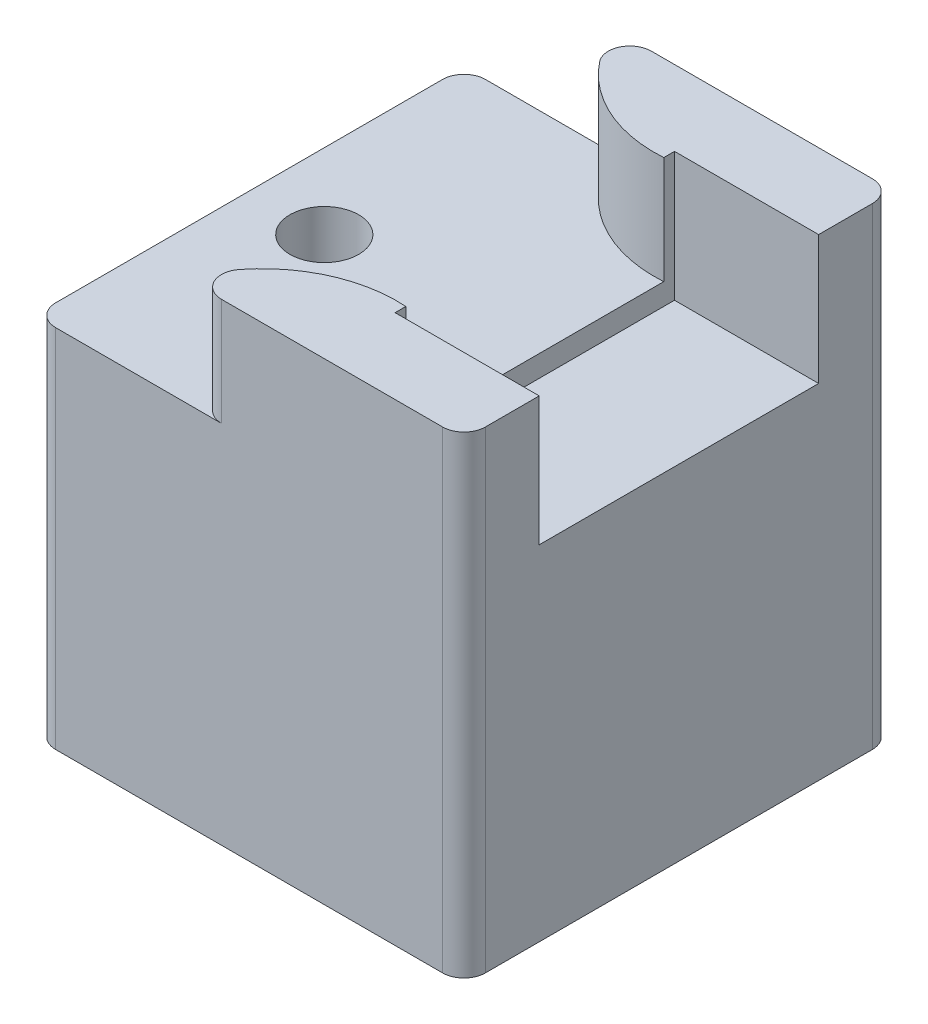
SolidWorks part; units mm, degrees
ref_plane "Alzado" through (0, 0, 0) normal (0, 0, 1) x (1, 0, 0)
ref_plane "Planta" through (0, 0, 0) normal (0, 1, 0) x (1, 0, 0)
ref_plane "Vista lateral" through (0, 0, 0) normal (1, 0, 0) x (0, 0, -1)
sketch "Croquis2" plane through (0, 0, 0) normal (0, 1, 0) x (1, 0, 0)
  line L1 (-10.8434, 8.4739) -> (9.1566, 8.4739)
  line L2 (-10.8434, 8.4739) -> (-10.8434, -11.5261)
  line L3 (-10.8434, -11.5261) -> (9.1566, -11.5261)
  line L4 (9.1566, 8.4739) -> (9.1566, -11.5261)
  dimension "D1" = 20
  dimension "D2" = 20
extrude "Saliente-Extruir1" add sketch "Croquis2" along normal blind 8
sketch "Croquis3" plane through (0, 8, 0) normal (0, 1, 0) x (1, 0, 0)
  line L0 (9.1566, 4.9739) -> (1.1799, 4.9739) construction
  line L1 (9.1566, -11.5261) -> (9.1566, 8.4739) construction
  line L2 (9.1566, -8.0261) -> (5.7192, -8.0261) construction
  line L3 (-10.8434, -11.5261) -> (9.1566, -11.5261) construction
  line L4 (9.1566, 8.4739) -> (-10.8434, 8.4739) construction
  line L6 (9.1566, 4.9739) -> (2.4509, 4.9739)
  line L7 (9.1566, 4.9739) -> (9.1566, -8.0261)
  line L8 (9.1566, -8.0261) -> (2.4509, -8.0261)
  line L9 (2.4509, 4.9739) -> (2.4509, -8.0261)
  dimension "D1" = 3.5
  dimension "D2" = 3.5
extrude "Cortar-Extruir1" cut sketch "Croquis3" against normal blind 6
sketch "Croquis5" plane through (0, 8, 0) normal (0, 1, 0) x (1, 0, 0)
  line L0 (2.4509, 4.9739) -> (-1.2584, 4.9739) construction
  line L1 (2.4509, -8.0261) -> (0, -8.0261) construction
  line L2 (2.4509, 4.9739) -> (2.4509, -8.0261) construction
  line L3 (2.4509, 4.4739) -> (1.59, 4.4739)
  line L4 (2.4509, 4.4739) -> (2.4509, -7.5261)
  line L5 (2.4509, -7.5261) -> (1.59, -7.5261)
  line L7 (-10.8434, 8.4739) -> (9.1566, -11.5261) construction
  line L8 (-0.8434, -1.5261) -> (2.4509, -1.5261) construction
  line L9 (9.1566, 8.4739) -> (-10.8434, 8.4739) construction
  arc A0 (2.4509, 4.4739) -> (-3.8325, 8.4739) centre (2.0204, 10.7329) cw
  arc A1 (2.4509, -7.5261) -> (-3.8325, -11.5261) centre (2.0204, -13.7851) ccw
  line M7 (2.4509, -8.0261) -> (2.4509, 4.9739)
  line M10 (9.1566, 8.4739) -> (-10.8434, 8.4739)
  line M11 (-10.8434, 8.4739) -> (-10.8434, -11.5261)
  line M12 (-10.8434, -11.5261) -> (9.1566, -11.5261)
  dimension "D2" = 12
extrude "Cortar-Extruir2" cut sketch "Croquis5" against normal blind 5 contours A1 A0 M7 M10 M11 M12
sketch "Croquis6" plane through (0, 3, 0) normal (0, 1, 0) x (1, 0, 0)
  line L0 (-7.3434, 8.4739) -> (-7.3434, -11.5261) construction
  line L1 (-3.8325, 8.4739) -> (-10.8434, 8.4739) construction
  line L2 (-10.8434, -11.5261) -> (-3.8325, -11.5261) construction
  line L3 (-10.8434, 8.4739) -> (-10.8434, -11.5261) construction
  circle A0 centre (-7.3434, -1.5261) radius 1.6
  dimension "D2" = 3.2
  dimension "D1" = 3.5
extrude "Cortar-Extruir3" cut sketch "Croquis6" against normal blind 3
fillet "Redondeo1" radius 1 6 edges at (-3.8325, 5.5, -8.4739) (-3.8325, 5.5, 11.5261) (9.1566, 4, -8.4739) (-10.8434, 1.5, -8.4739) (-10.8434, 1.5, 11.5261) (9.1566, 4, 11.5261)
sketch "Croquis7" plane through (0, 0, 0) normal (0, -1, 0) x (1, 0, 0)
  line L4 (-9.8434, -8.4739) -> (8.1566, -8.4739)
  line L5 (9.1566, -7.4739) -> (9.1566, 10.5261)
  line L6 (8.1566, 11.5261) -> (-9.8434, 11.5261)
  line L7 (-10.8434, 10.5261) -> (-10.8434, -7.4739)
  line L8 (-9.8434, -8.4739) -> (8.1566, -8.4739)
  line L9 (9.1566, -7.4739) -> (9.1566, 10.5261)
  line L10 (8.1566, 11.5261) -> (-9.8434, 11.5261)
  line L11 (-10.8434, 10.5261) -> (-10.8434, -7.4739)
  circle A0 centre (-7.3434, 1.5261) radius 1.6 construction
  circle A1 centre (-7.3434, 1.5261) radius 1.6
  arc A4 (8.1566, -8.4739) -> (9.1566, -7.4739) centre (8.1566, -7.4739) ccw
  arc A5 (9.1566, 10.5261) -> (8.1566, 11.5261) centre (8.1566, 10.5261) ccw
  arc A6 (-9.8434, 11.5261) -> (-10.8434, 10.5261) centre (-9.8434, 10.5261) ccw
  arc A7 (-10.8434, -7.4739) -> (-9.8434, -8.4739) centre (-9.8434, -7.4739) ccw
  arc A8 (8.1566, -8.4739) -> (9.1566, -7.4739) centre (8.1566, -7.4739) ccw
  arc A9 (9.1566, 10.5261) -> (8.1566, 11.5261) centre (8.1566, 10.5261) ccw
  arc A10 (-9.8434, 11.5261) -> (-10.8434, 10.5261) centre (-9.8434, 10.5261) ccw
  arc A11 (-10.8434, -7.4739) -> (-9.8434, -8.4739) centre (-9.8434, -7.4739) ccw
  dimension "D1" = 0
extrude "Saliente-Extruir2" add sketch "Croquis7" along normal blind 14
